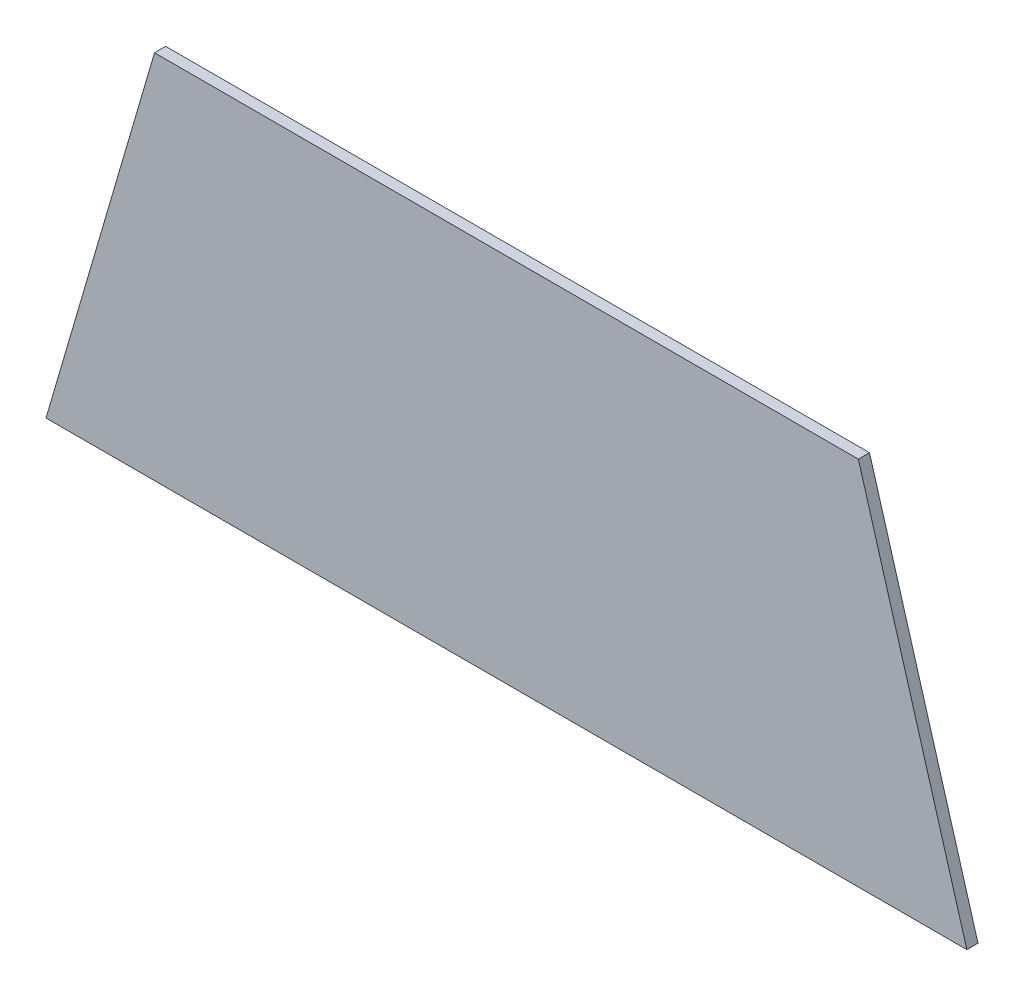
SolidWorks part; units mm, degrees
ref_plane "Front Plane" through (0, 0, 0) normal (0, 0, 1) x (1, 0, 0)
ref_plane "Top Plane" through (0, 0, 0) normal (0, 1, 0) x (1, 0, 0)
ref_plane "Right Plane" through (0, 0, 0) normal (1, 0, 0) x (0, 0, -1)
sketch "Sketch1" plane through (0, 0, 0) normal (0, 0, 1) x (1, 0, 0)
  line L0 (-3.5, 0) -> (245, 0)
  line L3 (149.129, 0) -> (149.129, 100) construction
  line L5 (-3.5, 0) -> (25.7799, 100)
  line L6 (245, 0) -> (215.7201, 100)
  line L7 (25.7799, 100) -> (215.7201, 100)
extrude "Boss-Extrude1" add sketch "Sketch1" along normal blind 3 and the other way blind 0.0067
